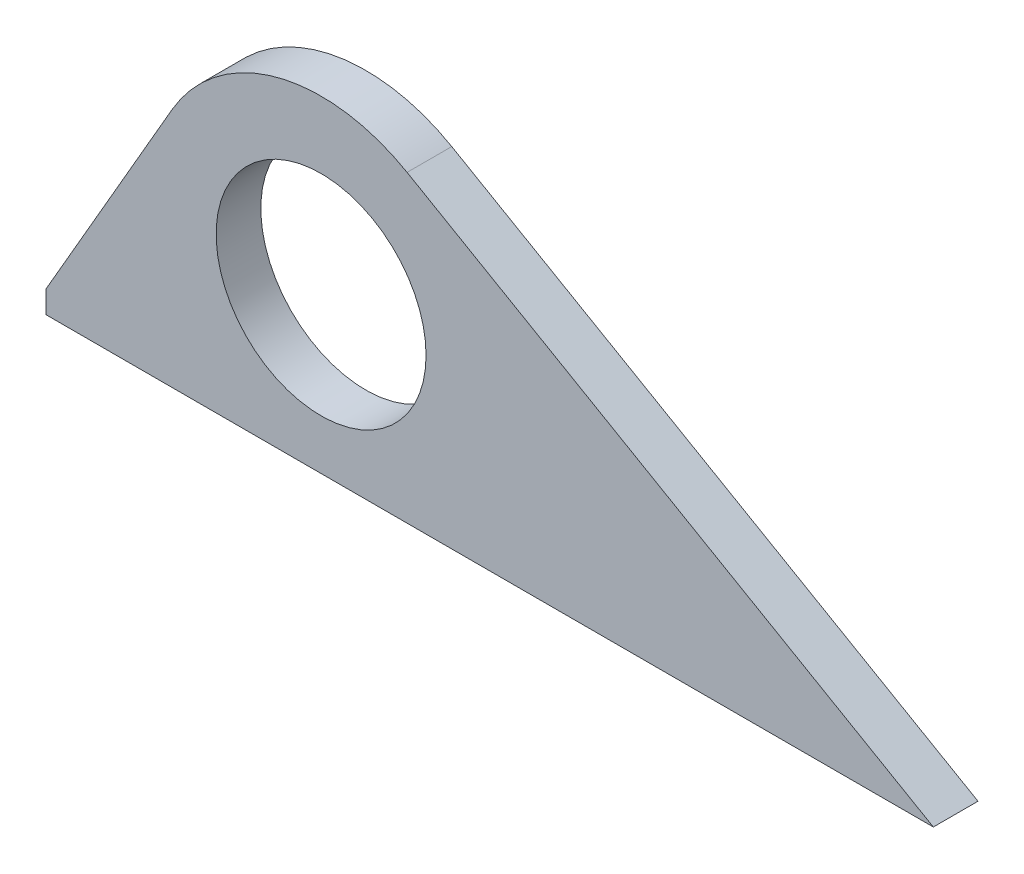
SolidWorks part; units mm, degrees
ref_plane "Plan de face" through (0, 0, 0) normal (0, 0, 1) x (1, 0, 0)
ref_plane "Plan de dessus" through (0, 0, 0) normal (0, 1, 0) x (1, 0, 0)
ref_plane "Plan de droite" through (0, 0, 0) normal (1, 0, 0) x (0, 0, -1)
sketch "Esquisse1" plane through (0, 0, 0) normal (0, 0, 1) x (1, 0, 0)
  line L0 (0, 0) -> (190, 0)
  line L1 (190, 0) -> (190, 5) construction
  line L2 (190, 5) -> (120.718, 45) construction
  line L3 (120.718, 45) -> (23.094, 45) construction
  line L4 (23.094, 45) -> (0, 5) construction
  line L5 (0, 5) -> (0, 0)
  line L6 (0, 5) -> (190, 5) construction
  line L7 (71.906, 45) -> (71.906, 5) construction
  line L8 (190, 5) -> (47.5, 87.2724) construction
  line L9 (0, 5) -> (47.5, 87.2724) construction
  line L10 (190, 5) -> (80.842, 68.0224)
  line L11 (28.25, 53.9304) -> (0, 5)
  line L12 (190, 0) -> (198.6603, 0)
  line L13 (198.6603, 0) -> (190, 5)
  arc A0 (28.25, 53.9304) -> (80.842, 68.0224) centre (61.592, 34.6804) cw
  circle A1 centre (61.592, 34.6804) radius 23.5
  dimension "D6" = 15
  dimension "D8" = 47
  dimension "D5" = 40
  dimension "D1" = 5
  dimension "D2" = 190
  dimension "D3" = 60
  dimension "D4" = 30
extrude "Boss.-Extru.1" add sketch "Esquisse1" along normal blind 10
